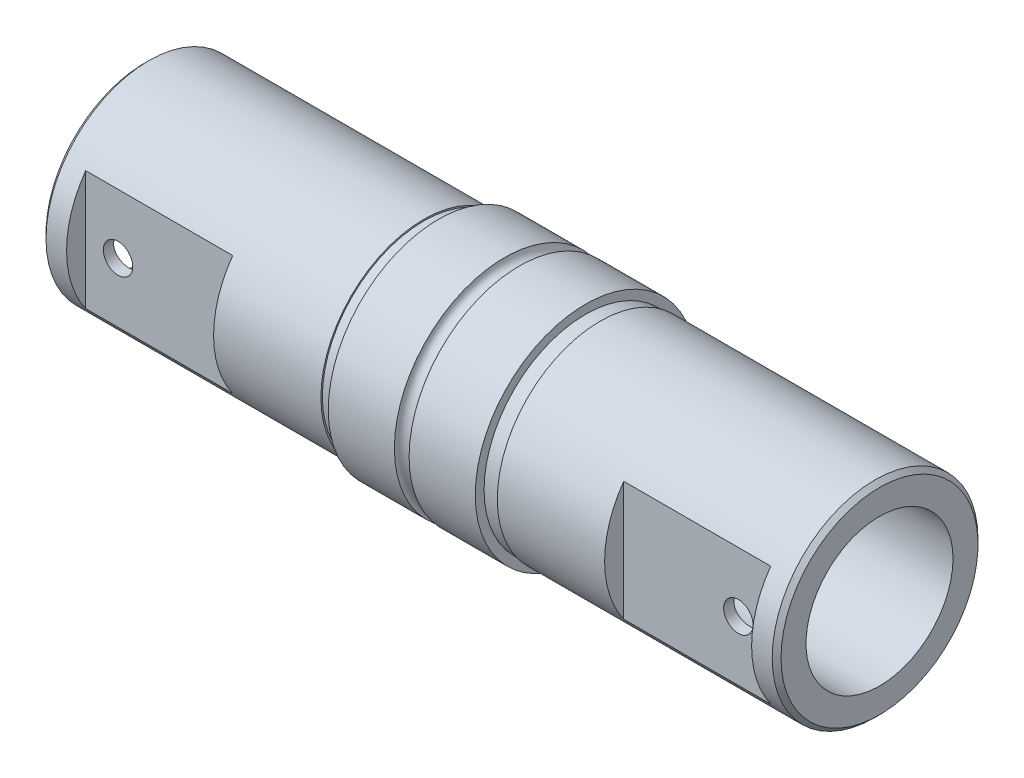
SolidWorks part; units mm, degrees
ref_plane "Alzado" through (0, 0, 0) normal (0, 0, 1) x (1, 0, 0)
ref_plane "Planta" through (0, 0, 0) normal (0, 1, 0) x (1, 0, 0)
ref_plane "Vista lateral" through (0, 0, 0) normal (1, 0, 0) x (0, 0, -1)
sketch "Croquis1" plane through (0, 0, 0) normal (0, 1, 0) x (1, 0, 0)
  line L0 (0, 12.3292) -> (0, -12.3292) construction
  line L1 (-200, 0) -> (200, 0) construction
  line L2 (-25, 37.5) -> (25, 37.5)
  line L3 (-25, 37.5) -> (-25, 35)
  line L4 (-125, 0) -> (125, 0)
  line L5 (-25, 35) -> (-125, 35)
  line L6 (-125, 35) -> (-125, 0)
  line L7 (25, 37.5) -> (25, 35)
  line L8 (25, 35) -> (125, 35)
  line L9 (125, 35) -> (125, 0)
  point P2 (0, 0)
  point P4 (0, 0)
  point P6 (0, 37.5)
  point P12 (0, -39.0099)
  point P15 (-25, 37.5)
  dimension "D1" = 50
  dimension "D2" = 70
  dimension "D3" = 75
  dimension "D5" = 70
  dimension "D6" = 125
  dimension "D7" = 250
revolve "Revolución1" add sketch "Croquis1" angle 360 about L1
chamfer "Chaflán2" distance 1.5 angle 45 1 edges at (-125, 0, 35)
chamfer "Chaflán3" distance 1.5 angle 45 1 edges at (125, 0, 35)
sketch "Croquis2" plane through (0, 0, 0) normal (0, 0, 1) x (1, 0, 0)
  line L0 (0, 0) -> (0, 58.2331) construction
  line L5 (-25, 37.5) -> (25, 37.3205) construction
  line L7 (-25, 35) -> (-30, 35)
  line L8 (-25, 35) -> (-25, 34.5)
  line L9 (-25, 34.5) -> (-30, 34.5)
  line L10 (-30, 35) -> (-30, 34.5)
  line L11 (25, 35) -> (30, 35)
  line L12 (25, 35) -> (25, 34.5)
  line L13 (25, 34.5) -> (30, 34.5)
  line L14 (30, 35) -> (30, 34.5)
  line L15 (25, -37.5) -> (25, 37.5) construction
  line L16 (25, 37.5) -> (-25, 37.5) construction
  circle A1 centre (0, 37.5) radius 2.5
  point P16 (-25, 37.5)
  point P17 (0, 0)
  point P18 (0, 37.5)
  dimension "D4" = 5
  dimension "D6" = 5
  dimension "D1" = 0.5
  dimension "D2" = 5
  dimension "D3" = 5
  dimension "D5" = 0.5
revolve "Cortar-Revolución1" cut sketch "Croquis2" angle 360 about L1
ref_plane "Plano1" through (0, 0, 35) normal (0, 0, 1) x (1, 0, 0)
sketch "Croquis3" plane through (0, 0, 35) normal (0, 0, 1) x (1, 0, 0)
  line L0 (-123.5, 35) -> (-123.5, -35) construction
  line L1 (66.5, 25) -> (116.5, 25)
  line L2 (66.5, 25) -> (66.5, -25)
  line L3 (66.5, -25) -> (116.5, -25)
  line L4 (116.5, 25) -> (116.5, -25)
  line L5 (-116.5, 25) -> (-66.5, 25)
  line L6 (-116.5, 25) -> (-116.5, -25)
  line L7 (-116.5, -25) -> (-66.5, -25)
  line L8 (-66.5, 25) -> (-66.5, -25)
  line L9 (123.5, 35) -> (123.5, -35) construction
  line L10 (-25, 0) -> (-125, 0) construction
  line L11 (25, 0) -> (125, 0) construction
  circle A1 centre (-105.5, 0) radius 5
  circle A2 centre (-80.5, 0) radius 5
  circle A3 centre (80.5, 0) radius 5
  circle A4 centre (105.5, 0) radius 5
  point P24 (0, 0)
  point P26 (75.5066, 1.2202)
  dimension "D7" = 80.5
  dimension "D1" = 7
  dimension "D2" = 50
  dimension "D3" = 7
  dimension "D5" = 50
  dimension "D6" = 50
  dimension "D8" = 80.5
  dimension "D9" = 105.5
  dimension "D10" = 105.5
sketch "Croquis5" plane through (125, 0, 0) normal (1, 0, 0) x (0, 0, -1)
  circle A0 centre (0, 0) radius 25
extrude "Cortar-Extruir5" cut sketch "Croquis5" against normal blind 300
extrude "Cortar-Extruir9" cut sketch "Croquis3" against normal blind 6.5 contours L2 L3 L4 L1 | L7 L8 L5 L6
sketch "Croquis7" plane through (0, 0, 28.5) normal (0, 0, 1) x (1, 0, 0)
  line L0 (-25, 0) -> (-125, 0) construction
  line L1 (25, 0) -> (125, 0) construction
  circle A0 centre (-105.5, 0) radius 5
  circle A1 centre (105.5, 0) radius 5
  dimension "D1" = 105.5
  dimension "D2" = 105.5
extrude "Cortar-Extruir12" cut sketch "Croquis7" against normal blind 46.5
